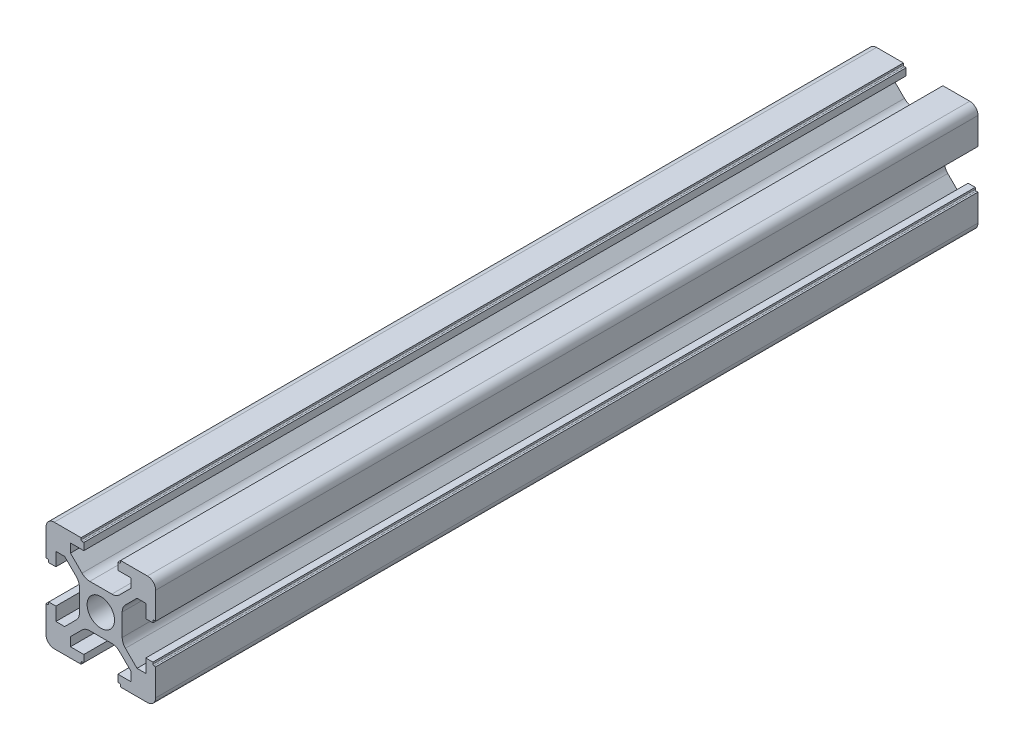
SolidWorks part; units mm, degrees
material "6063-T6"
ref_plane "Спереди" through (0, 0, 0) normal (0, 0, 1) x (1, 0, 0)
ref_plane "Сверху" through (0, 0, 0) normal (0, 1, 0) x (1, 0, 0)
ref_plane "Справа" through (0, 0, 0) normal (1, 0, 0) x (0, 0, -1)
sketch "Sketch1" plane through (0, 0, 0) normal (0, 0, 1) x (1, 0, 0)
  line L0 (0, 10) -> (0, -10) construction
  line L1 (-10, -10) -> (10, -10) construction
  line L2 (-10, -10) -> (-10, 10) construction
  line L3 (-10, 10) -> (10, 10) construction
  line L4 (10, -10) -> (10, 10) construction
  line L5 (-10, -10) -> (10, 10) construction
  line L6 (-10, 10) -> (10, -10) construction
  line L7 (-10, 0) -> (10, 0) construction
  line L8 (0, 3.9) -> (-2.0109, 3.9)
  line L9 (-3.4251, 4.4858) -> (-5.5393, 6.6)
  line L10 (-5.5393, 6.6) -> (-5.5393, 8.2)
  line L11 (-5.5393, 8.2) -> (-3.1, 8.2)
  line L12 (-3.1, 8.2) -> (-3.1, 9.5)
  line L13 (-3.1, 9.5) -> (-3.4, 9.5)
  line L14 (-3.6, 9.7) -> (-3.6, 10)
  line L15 (-3.6, 10) -> (-8.5, 10)
  line L16 (-10, 3.6) -> (-10, 8.5)
  line L17 (-9.7, 3.6) -> (-10, 3.6)
  line L18 (-9.5, 3.1) -> (-9.5, 3.4)
  line L19 (-8.2, 3.1) -> (-9.5, 3.1)
  line L20 (-8.2, 5.5393) -> (-8.2, 3.1)
  line L21 (-6.6, 5.5393) -> (-8.2, 5.5393)
  line L22 (-4.4858, 3.4251) -> (-6.6, 5.5393)
  line L23 (-3.9, 0) -> (-3.9, 2.0109)
  line L24 (3.9, 0) -> (3.9, 2.0109)
  line L25 (4.4858, 3.4251) -> (6.6, 5.5393)
  line L26 (6.6, 5.5393) -> (8.2, 5.5393)
  line L27 (8.2, 5.5393) -> (8.2, 3.1)
  line L28 (8.2, 3.1) -> (9.5, 3.1)
  line L29 (9.5, 3.1) -> (9.5, 3.4)
  line L30 (9.7, 3.6) -> (10, 3.6)
  line L31 (10, 3.6) -> (10, 8.5)
  line L32 (3.6, 10) -> (8.5, 10)
  line L33 (3.6, 9.7) -> (3.6, 10)
  line L34 (3.1, 9.5) -> (3.4, 9.5)
  line L35 (3.1, 8.2) -> (3.1, 9.5)
  line L36 (5.5393, 8.2) -> (3.1, 8.2)
  line L37 (5.5393, 6.6) -> (5.5393, 8.2)
  line L38 (3.4251, 4.4858) -> (5.5393, 6.6)
  line L39 (0, 3.9) -> (2.0109, 3.9)
  line L40 (0, -3.9) -> (2.0109, -3.9)
  line L41 (3.4251, -4.4858) -> (5.5393, -6.6)
  line L42 (5.5393, -6.6) -> (5.5393, -8.2)
  line L43 (5.5393, -8.2) -> (3.1, -8.2)
  line L44 (3.1, -8.2) -> (3.1, -9.5)
  line L45 (3.1, -9.5) -> (3.4, -9.5)
  line L46 (3.6, -9.7) -> (3.6, -10)
  line L47 (3.6, -10) -> (8.5, -10)
  line L48 (10, -3.6) -> (10, -8.5)
  line L49 (9.7, -3.6) -> (10, -3.6)
  line L50 (9.5, -3.1) -> (9.5, -3.4)
  line L51 (8.2, -3.1) -> (9.5, -3.1)
  line L52 (8.2, -5.5393) -> (8.2, -3.1)
  line L53 (6.6, -5.5393) -> (8.2, -5.5393)
  line L54 (4.4858, -3.4251) -> (6.6, -5.5393)
  line L55 (3.9, 0) -> (3.9, -2.0109)
  line L56 (-3.9, 0) -> (-3.9, -2.0109)
  line L57 (-4.4858, -3.4251) -> (-6.6, -5.5393)
  line L58 (-6.6, -5.5393) -> (-8.2, -5.5393)
  line L59 (-8.2, -5.5393) -> (-8.2, -3.1)
  line L60 (-8.2, -3.1) -> (-9.5, -3.1)
  line L61 (-9.5, -3.1) -> (-9.5, -3.4)
  line L62 (-9.7, -3.6) -> (-10, -3.6)
  line L63 (-10, -3.6) -> (-10, -8.5)
  line L64 (-3.6, -10) -> (-8.5, -10)
  line L65 (-3.6, -9.7) -> (-3.6, -10)
  line L66 (-3.1, -9.5) -> (-3.4, -9.5)
  line L67 (-3.1, -8.2) -> (-3.1, -9.5)
  line L68 (-5.5393, -8.2) -> (-3.1, -8.2)
  line L69 (-5.5393, -6.6) -> (-5.5393, -8.2)
  line L70 (-3.4251, -4.4858) -> (-5.5393, -6.6)
  line L71 (0, -3.9) -> (-2.0109, -3.9)
  circle A0 centre (0, 0) radius 2.5
  arc A1 (-8.5, 10) -> (-10, 8.5) centre (-8.5, 8.5) ccw
  arc A2 (-2.0109, 3.9) -> (-3.4251, 4.4858) centre (-2.0109, 5.9) cw
  arc A3 (-3.4, 9.5) -> (-3.6, 9.7) centre (-3.4, 9.7) cw
  arc A4 (-9.5, 3.4) -> (-9.7, 3.6) centre (-9.7, 3.4) ccw
  arc A5 (-3.9, 2.0109) -> (-4.4858, 3.4251) centre (-5.9, 2.0109) ccw
  arc A6 (10, 8.5) -> (8.5, 10) centre (8.5, 8.5) ccw
  arc A7 (3.9, 2.0109) -> (4.4858, 3.4251) centre (5.9, 2.0109) cw
  arc A8 (9.5, 3.4) -> (9.7, 3.6) centre (9.7, 3.4) cw
  arc A9 (3.4, 9.5) -> (3.6, 9.7) centre (3.4, 9.7) ccw
  arc A10 (2.0109, 3.9) -> (3.4251, 4.4858) centre (2.0109, 5.9) ccw
  arc A11 (8.5, -10) -> (10, -8.5) centre (8.5, -8.5) ccw
  arc A12 (2.0109, -3.9) -> (3.4251, -4.4858) centre (2.0109, -5.9) cw
  arc A13 (3.4, -9.5) -> (3.6, -9.7) centre (3.4, -9.7) cw
  arc A14 (9.5, -3.4) -> (9.7, -3.6) centre (9.7, -3.4) ccw
  arc A15 (3.9, -2.0109) -> (4.4858, -3.4251) centre (5.9, -2.0109) ccw
  arc A16 (-10, -8.5) -> (-8.5, -10) centre (-8.5, -8.5) ccw
  arc A17 (-3.9, -2.0109) -> (-4.4858, -3.4251) centre (-5.9, -2.0109) cw
  arc A18 (-9.5, -3.4) -> (-9.7, -3.6) centre (-9.7, -3.4) cw
  arc A19 (-3.4, -9.5) -> (-3.6, -9.7) centre (-3.4, -9.7) ccw
  arc A20 (-2.0109, -3.9) -> (-3.4251, -4.4858) centre (-2.0109, -5.9) ccw
  point P0 (0, 0)
  point P42 (0, 0)
  point P70 (0, 0)
  point P98 (0, 0)
  point P126 (0, 0)
  dimension "D3" = 5
  dimension "D4" = 3
  dimension "D12" = 2
  dimension "D13" = 0.2
  dimension "D1" = 20
  dimension "D2" = 20
  dimension "D5" = 6.2
  dimension "D6" = 7.2
  dimension "D7" = 1.8
  dimension "D8" = 0.5
  dimension "D9" = 3.4
  dimension "D10" = 1.5
  dimension "D11" = 6.1
  dimension "D14" = 4
extrude "Extrude1" add sketch "Sketch1" along normal blind 150
